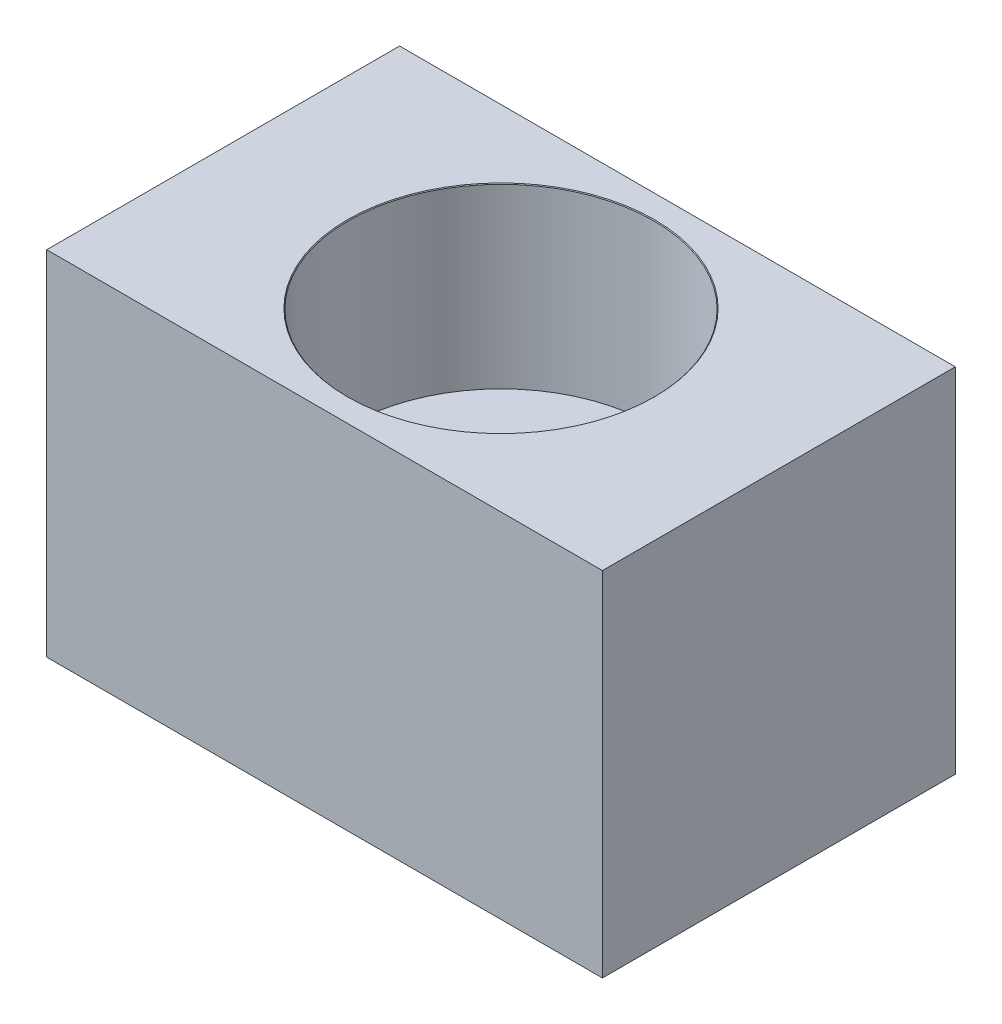
SolidWorks part; units mm, degrees
ref_plane "Alzado" through (0, 0, 0) normal (0, 0, 1) x (1, 0, 0)
ref_plane "Planta" through (0, 0, 0) normal (0, 1, 0) x (1, 0, 0)
ref_plane "Vista lateral" through (0, 0, 0) normal (1, 0, 0) x (0, 0, -1)
sketch "Croquis1" plane through (0, 0, 0) normal (0, 0, 1) x (1, 0, 0)
  line L1 (10, 6.35) -> (-10, 6.35)
  line L2 (10, 6.35) -> (10, -6.35)
  line L3 (10, -6.35) -> (-10, -6.35)
  line L4 (-10, 6.35) -> (-10, -6.35)
  line L5 (10, 6.35) -> (-10, -6.35) construction
  line L6 (10, -6.35) -> (-10, 6.35) construction
  point P0 (0, 0)
  dimension "D1" = 20
  dimension "D2" = 12.7
extrude "Saliente-Extruir1" add sketch "Croquis1" along normal mid plane 12.7
hole_wizard "Refrentado para tornillo con cabeza hueca de M61" positions "Croquis2" profile "Croquis3" counterbore size "M6" standard "DIN" end condition through all
sketch "Croquis2" plane through (0, 6.35, 0) normal (0, 1, 0) x (1, 0, 0)
  point P0 (0, 0)
  point P3 (-15.1698, 1.0587)
  point P4 (0, 0)
  dimension "D1" = 10
sketch "Croquis3" plane through (0, 6.35, 0) normal (1, 0, 0) x (0, 0, 1)
  line L0 (0, 0) -> (0, 12.7)
  line L1 (3.3, 12.675) -> (3.325, 12.7)
  line L2 (5.5, 6.4) -> (3.3, 6.4)
  line L3 (3.3, 6.4) -> (3.3, 12.675)
  line L5 (5.5, 6.4) -> (5.5, 0.025)
  line L6 (5.5, 0.025) -> (5.525, 0)
  line L7 (5.525, 0) -> (0, 0)
  line L8 (-5.5, 0.025) -> (-5.525, 0) construction
  line L11 (0, -6.35) -> (0, 107.95) construction
  line L12 (3.325, 12.7) -> (0, 12.7)
  line L13 (-3.3, 12.675) -> (-3.325, 12.7) construction
  dimension "Diámetro de taladro hasta el siguiente" = 6.6
  dimension "Profundidad de taladro hasta el siguiente" = 12.7
  dimension "Diámetro de refrentado" = 11
  dimension "Profundidad de refrentado" = 6.4
  dimension "Diámetro de avellanado cercano" = 11.05
  dimension "Ángulo de avellanado cercano" = 90
  dimension "Diámetro de avellanado lejano" = 6.65
  dimension "Ángulo de avellanado lejano" = 90
